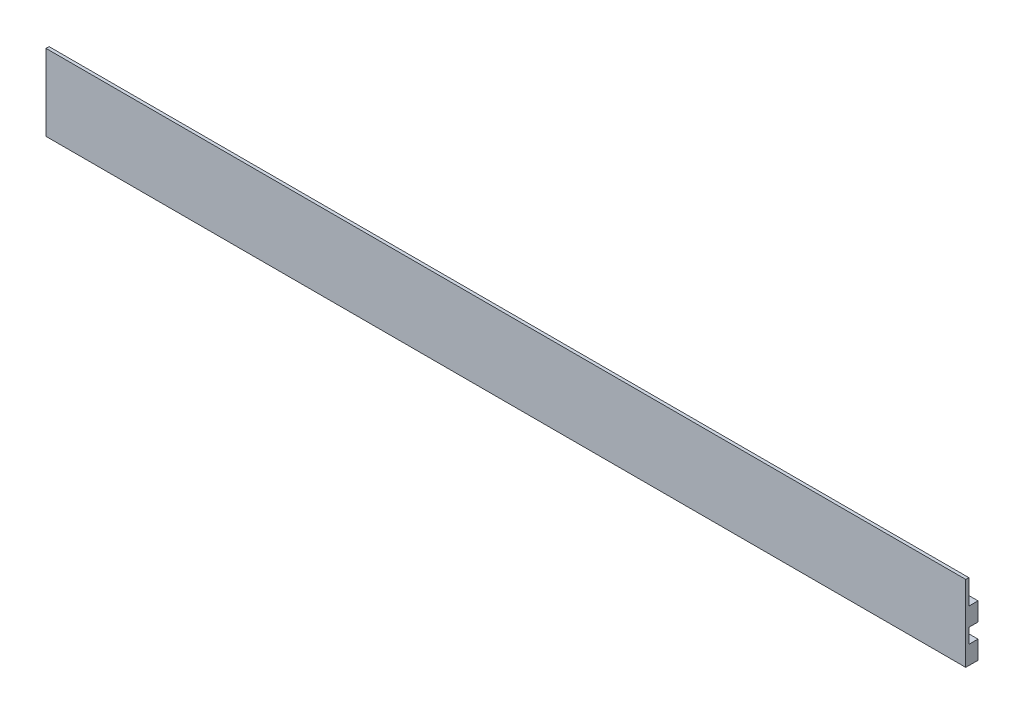
SolidWorks part; units mm, degrees
ref_plane "Front Plane" through (0, 0, 0) normal (0, 0, 1) x (1, 0, 0)
ref_plane "Top Plane" through (0, 0, 0) normal (0, 1, 0) x (1, 0, 0)
ref_plane "Right Plane" through (0, 0, 0) normal (1, 0, 0) x (0, 0, -1)
sketch "Sketch1" plane through (0, 0, 0) normal (0, 0, 1) x (1, 0, 0)
  line L1 (1500, -550) -> (-1500, -550)
  line L2 (1500, -550) -> (1500, 550)
  line L3 (1500, 550) -> (-1500, 550)
  line L4 (-1500, -550) -> (-1500, 550)
  line L5 (1500, -550) -> (-1500, 550) construction
  line L6 (1500, 550) -> (-1500, -550) construction
  point P0 (0, 0)
  dimension "D1" = 1100
  dimension "D2" = 3000
extrude "Boss-Extrude1" add sketch "Sketch1" along normal mid plane 10
sketch "Sketch3" plane through (0, 0, -5) normal (0, 0, -1) x (-1, 0, 0)
  line L0 (-1500, -550) -> (-1500, 550) construction
  line L1 (1500, 469.4716) -> (-1500, 469.4716)
  line L2 (1500, 469.4716) -> (1500, 409.4716)
  line L3 (1500, 409.4716) -> (-1500, 409.4716)
  line L4 (-1500, 469.4716) -> (-1500, 409.4716)
  line L5 (1500, 469.4716) -> (-1500, 409.4716) construction
  line L6 (1500, 409.4716) -> (-1500, 469.4716) construction
  line L7 (1500, 550) -> (1500, -550) construction
  line L8 (1500, 361.3466) -> (-1500, 361.3466)
  line L9 (1500, 361.3466) -> (1500, 301.3466)
  line L10 (1500, 301.3466) -> (-1500, 301.3466)
  line L11 (-1500, 361.3466) -> (-1500, 301.3466)
  line L12 (1500, 361.3466) -> (-1500, 301.3466) construction
  line L13 (1500, 301.3466) -> (-1500, 361.3466) construction
  point P0 (0, 439.4716)
  point P7 (0, 331.3466)
  dimension "D1" = 60
  dimension "60" = 60
extrude "Boss-Extrude3" add sketch "Sketch3" along normal blind 30
sketch "Sketch4" plane through (0, 0, -5) normal (0, 0, -1) x (-1, 0, 0)
  line L4 (1500, 301.3466) -> (-1500, 301.3466)
  line L5 (-1500, 301.3466) -> (-1500, -550)
  line L6 (-1500, -550) -> (1500, -550)
  line L7 (1500, -550) -> (1500, 301.3466)
  line L8 (1500, 301.3466) -> (-1500, 301.3466)
  line L9 (-1500, 301.3466) -> (-1500, -550)
  line L10 (-1500, -550) -> (1500, -550)
  line L11 (1500, -550) -> (1500, 301.3466)
  dimension "D1" = 0
extrude "Cut-Extrude1" cut sketch "Sketch4" against normal through all
